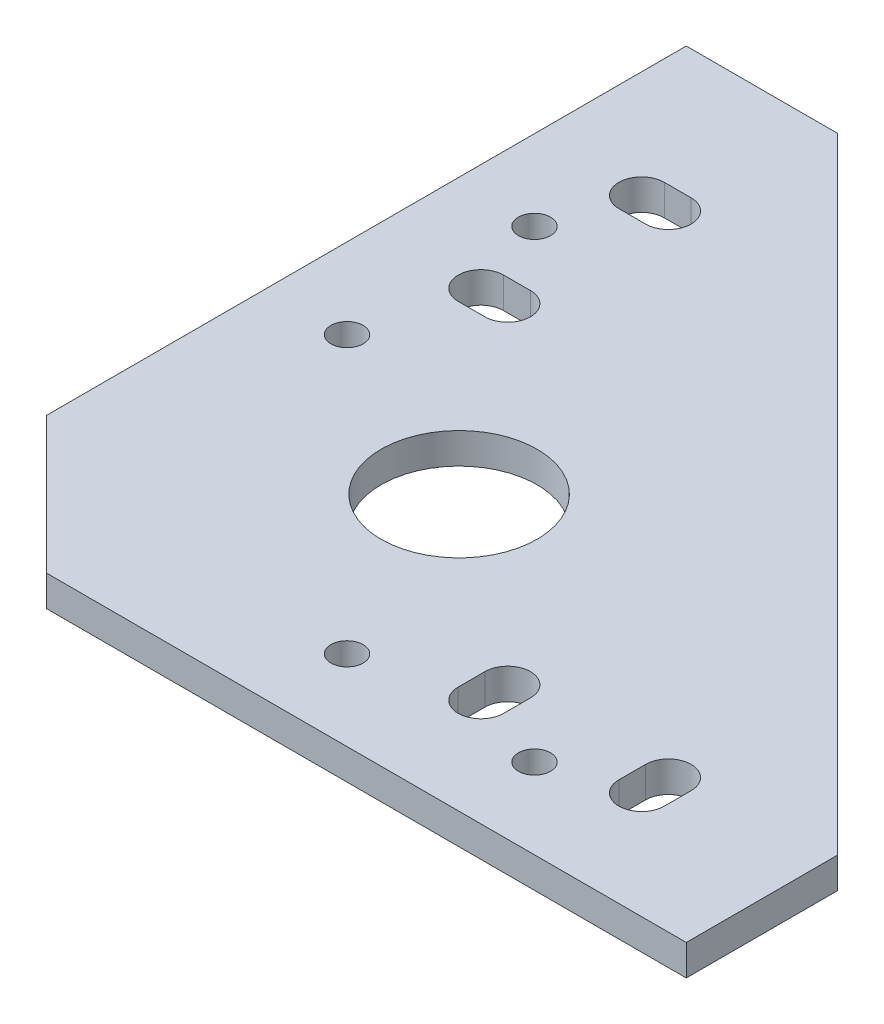
SolidWorks part; units mm, degrees
ref_plane "前视基准面" through (0, 0, 0) normal (0, 0, 1) x (1, 0, 0)
ref_plane "上视基准面" through (0, 0, 0) normal (0, 1, 0) x (1, 0, 0)
ref_plane "右视基准面" through (0, 0, 0) normal (1, 0, 0) x (0, 0, -1)
other "Configuration Table"
sketch "草图1" plane through (0, 0, 0) normal (0, 1, 0) x (1, 0, 0)
  line L0 (0, 0) -> (0, 144.96)
  line L1 (0, 144.96) -> (28.2843, 144.96)
  line L2 (28.2843, 144.96) -> (144.96, 28.2843)
  line L3 (144.96, 28.2843) -> (144.96, 0)
  line L4 (144.96, 0) -> (0, 0)
  line L5 (0, 25.4558) -> (25.4558, 0)
  line L6 (86.6188, 20) -> (86.6188, 25) construction
  line L7 (82.3688, 20) -> (82.3688, 25)
  line L8 (90.8688, 20) -> (90.8688, 25)
  line L9 (116.6188, 20) -> (116.6188, 25) construction
  line L10 (112.3688, 20) -> (112.3688, 25)
  line L11 (120.8688, 20) -> (120.8688, 25)
  line L12 (0, 0) -> (12.7279, 12.7279) construction
  line L13 (20, 116.6188) -> (25, 116.6188) construction
  line L14 (20, 112.3688) -> (25, 112.3688)
  line L15 (20, 120.8688) -> (25, 120.8688)
  line L16 (20, 86.6188) -> (25, 86.6188) construction
  line L17 (20, 82.3688) -> (25, 82.3688)
  line L18 (20, 90.8688) -> (25, 90.8688)
  line L19 (28.2843, 144.96) -> (0.9324, 172.3119)
  circle A0 centre (51.27, 51.27) radius 14.5685
  circle A1 centre (66.6188, 15) radius 3
  circle A2 centre (101.6188, 15) radius 3
  arc A3 (82.3688, 20) -> (90.8688, 20) centre (86.6188, 20) ccw
  arc A4 (90.8688, 25) -> (82.3688, 25) centre (86.6188, 25) ccw
  arc A5 (112.3688, 20) -> (120.8688, 20) centre (116.6188, 20) ccw
  arc A6 (120.8688, 25) -> (112.3688, 25) centre (116.6188, 25) ccw
  arc A7 (20, 112.3688) -> (20, 120.8688) centre (20, 116.6188) cw
  arc A8 (25, 120.8688) -> (25, 112.3688) centre (25, 116.6188) cw
  circle A9 centre (15, 101.6188) radius 3
  arc A10 (20, 82.3688) -> (20, 90.8688) centre (20, 86.6188) cw
  arc A11 (25, 90.8688) -> (25, 82.3688) centre (25, 86.6188) cw
  circle A12 centre (15, 66.6188) radius 3
  point P14 (86.6188, 22.5)
  point P21 (116.6188, 22.5)
  point P32 (22.5, 116.6188)
  point P41 (22.5, 86.6188)
  dimension "D1" = 51.27
  dimension "D2" = 93.69
  dimension "D6" = 30
  dimension "D8" = 15
  dimension "D9" = 51.27
  dimension "D10" = 6
  dimension "D11" = 4.25
  dimension "D14" = 73
  dimension "D15" = 35
  dimension "D3" = 36
  dimension "D4" = 135
  dimension "D5" = 30
  dimension "D7" = 20
  dimension "D12" = 20
  dimension "D13" = 25
  dimension "D16" = 20
extrude "凸台-拉伸1" add sketch "草图1" along normal blind 5.75 contours L0 L5 L4 L3 L2 L1 L18 A11 L17 A10 A9 A6 L11 A5 L10 A4 L8 A3 L7 A2 A1 A0 L15 A8 L14 A7 A12
